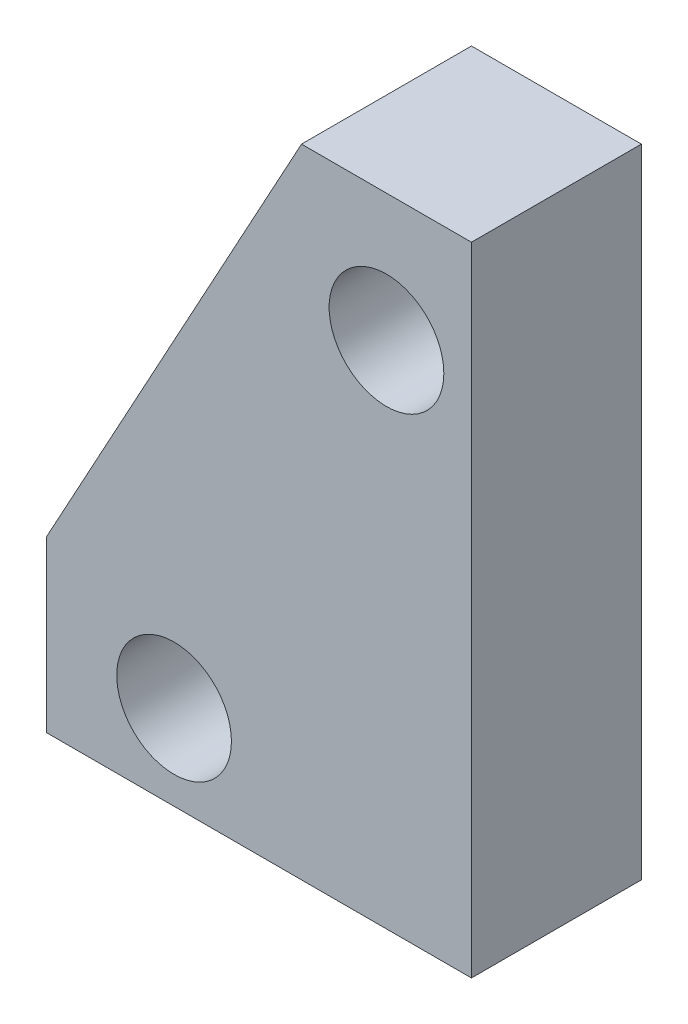
SolidWorks part; units mm, degrees
material "Aleación 1060"
ref_plane "Alzado" through (0, 0, 0) normal (0, 0, 1) x (1, 0, 0)
ref_plane "Planta" through (0, 0, 0) normal (0, 1, 0) x (1, 0, 0)
ref_plane "Vista lateral" through (0, 0, 0) normal (1, 0, 0) x (0, 0, -1)
sketch "Croquis1" plane through (0, 0, 0) normal (0, 0, 1) x (1, 0, 0)
  line L0 (-172.1331, 79.2019) -> (-162.1331, 79.2019)
  line L1 (-162.1331, 79.2019) -> (-162.1331, 94.2019)
  line L2 (-162.1331, 94.2019) -> (-166.1331, 94.2019)
  line L3 (-166.1331, 94.2019) -> (-172.1331, 83.2019)
  line L4 (-172.1331, 83.2019) -> (-172.1331, 79.2019)
  circle A0 centre (-169.1331, 81.2019) radius 1.35
  circle A1 centre (-164.1331, 91.2019) radius 1.35
  dimension "D1" = 2.7
  dimension "D3" = 2.7
  dimension "D2" = 3
  dimension "D4" = 3
  dimension "D5" = 15
  dimension "D6" = 10
  dimension "D7" = 2
  dimension "D8" = 2
  dimension "D9" = 4
  dimension "D10" = 4
  dimension "D11" = 90
  dimension "D12" = 90
extrude "Saliente-Extruir1" add sketch "Croquis1" along normal blind 4
